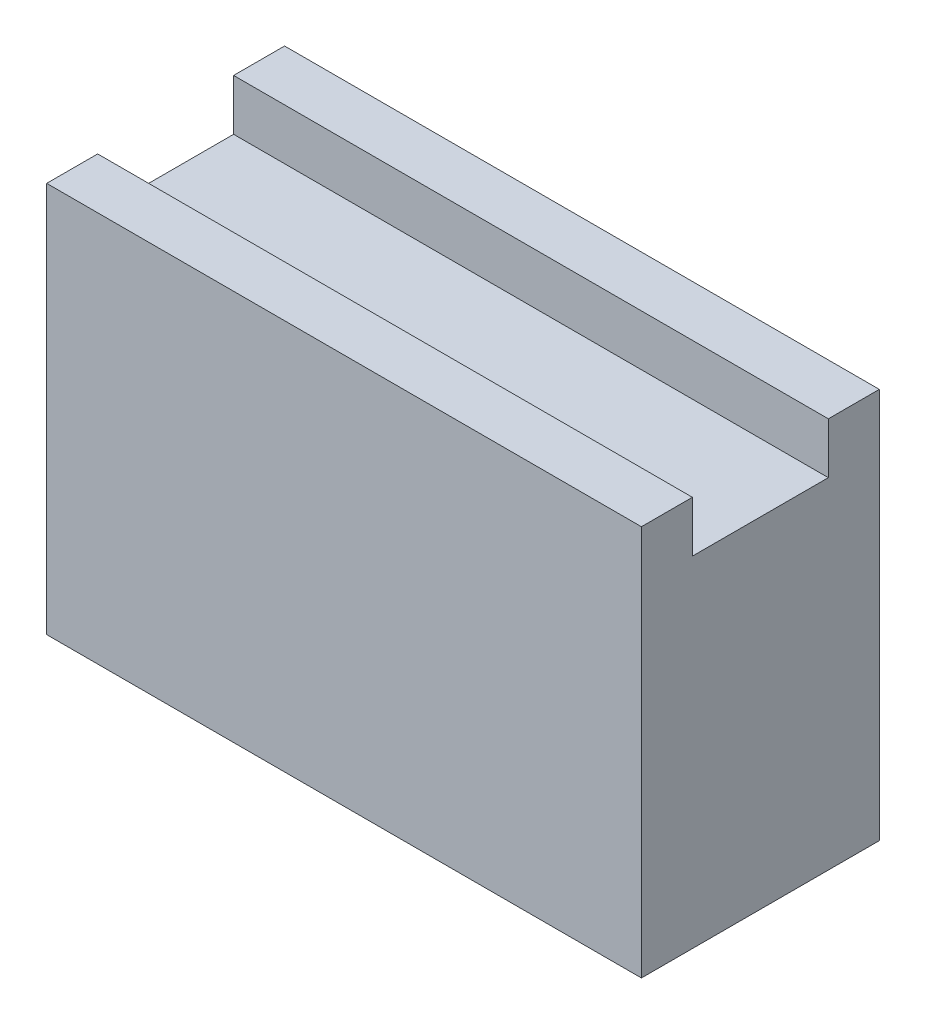
SolidWorks part; units mm, degrees
ref_plane "Front Plane" through (0, 0, 0) normal (0, 0, 1) x (1, 0, 0)
ref_plane "Top Plane" through (0, 0, 0) normal (0, 1, 0) x (1, 0, 0)
ref_plane "Right Plane" through (0, 0, 0) normal (1, 0, 0) x (0, 0, -1)
sketch "Sketch1" plane through (0, 0, 0) normal (1, 0, 0) x (0, 0, -1)
  line L0 (-7, 10) -> (-7, 13)
  line L1 (-7, -10) -> (7, -10)
  line L2 (-7, -10) -> (-7, 10)
  line L3 (-4, 10) -> (4, 10)
  line L4 (7, -10) -> (7, 10)
  line L5 (-7, -10) -> (7, 10) construction
  line L6 (-7, 10) -> (7, -10) construction
  line L7 (-7, 13) -> (-4, 13)
  line L8 (-4, 13) -> (-4, 10)
  line L9 (7, 10) -> (7, 13)
  line L10 (7, 13) -> (4, 13)
  line L11 (4, 13) -> (4, 10)
  point P0 (0, 0)
  point P12 (0, 10)
  dimension "D1" = 20
  dimension "D2" = 8
  dimension "D3" = 3
  dimension "D4" = 3
extrude "Boss-Extrude1" add sketch "Sketch1" against normal blind 35
